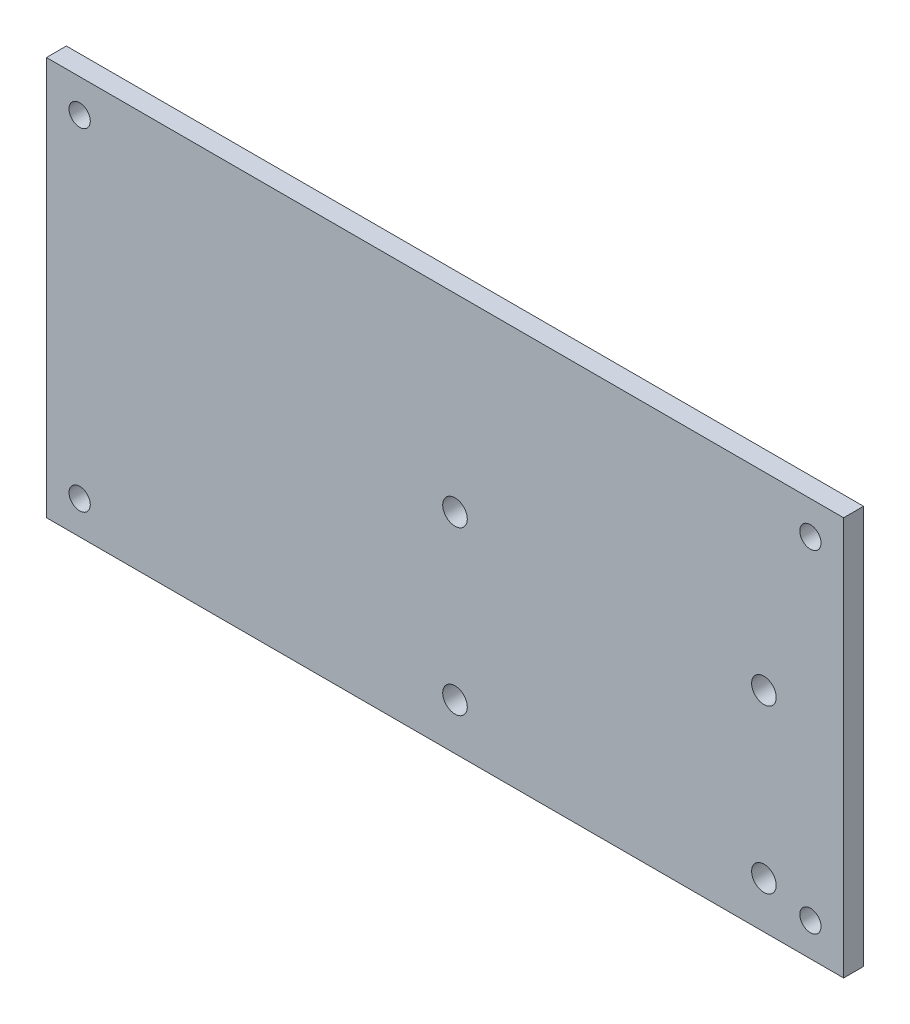
SolidWorks part; units mm, degrees
ref_plane "Front Plane" through (0, 0, 0) normal (0, 0, 1) x (1, 0, 0)
ref_plane "Top Plane" through (0, 0, 0) normal (0, 1, 0) x (1, 0, 0)
ref_plane "Right Plane" through (0, 0, 0) normal (1, 0, 0) x (0, 0, -1)
sketch "Sketch1" plane through (0, 0, 0) normal (0, 0, 1) x (1, 0, 0)
  line L1 (-56.9074, 24.37) -> (63.0926, 24.37)
  line L2 (-56.9074, 24.37) -> (-56.9074, -35.63)
  line L3 (-56.9074, -35.63) -> (63.0926, -35.63)
  line L4 (63.0926, 24.37) -> (63.0926, -35.63)
  dimension "D1" = 60
  dimension "D2" = 120
extrude "Boss-Extrude1" add sketch "Sketch1" along normal blind 3
sketch "Sketch3" plane through (0, 0, 3) normal (0, 0, 1) x (1, 0, 0)
  circle A0 centre (4.5926, -4.13) radius 1.85
  circle A1 centre (51.0926, -4.13) radius 1.85
  circle A2 centre (51.0926, -28.63) radius 1.85
  circle A3 centre (4.5926, -28.63) radius 1.85
  dimension "D1" = 3.7
  dimension "D2" = 3.7
  dimension "D3" = 3.7
  dimension "D4" = 3.7
extrude "Cut-Extrude1" cut sketch "Sketch3" against normal through all
sketch "Sketch4" plane through (0, 0, 3) normal (0, 0, 1) x (1, 0, 0)
  line L0 (-56.9074, 24.37) -> (-56.9074, -35.63) construction
  line L1 (63.0926, 24.37) -> (-56.9074, 24.37) construction
  line L2 (63.0926, -35.63) -> (63.0926, 24.37) construction
  line L3 (-56.9074, -35.63) -> (63.0926, -35.63) construction
  circle A1 centre (-51.9074, 19.37) radius 1.5
  circle A2 centre (58.0926, 19.37) radius 1.5
  circle A3 centre (58.0926, -30.63) radius 1.5
  circle A4 centre (-51.9074, -30.63) radius 1.5
  dimension "D1" = 5
  dimension "D2" = 5
  dimension "D5" = 5
  dimension "D6" = 5
  dimension "D3" = 2
  dimension "D4" = 2
extrude "Cut-Extrude2" cut sketch "Sketch4" against normal through all
sketch "Sketch5" plane through (0, 0, 0) normal (0, 0, -1) x (-1, 0, 0)
  circle A0 centre (-58.0926, 19.37) radius 1.6
  circle A1 centre (-58.0926, -30.63) radius 1.6
  circle A2 centre (51.9074, -30.63) radius 1.6
  circle A3 centre (51.9074, 19.37) radius 1.6
extrude "Cut-Extrude3" cut sketch "Sketch5" against normal blind 10
